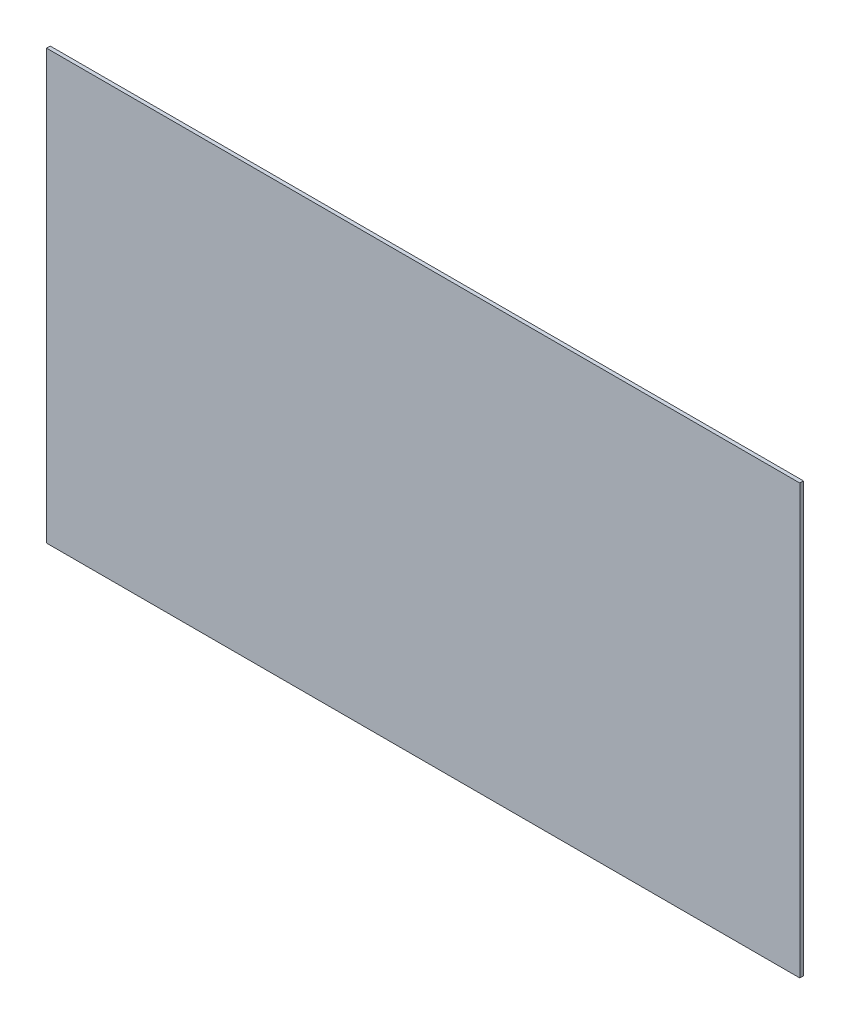
SolidWorks part; units mm, degrees
ref_plane "前视基准面" through (0, 0, 0) normal (0, 0, 1) x (1, 0, 0)
ref_plane "上视基准面" through (0, 0, 0) normal (0, 1, 0) x (1, 0, 0)
ref_plane "右视基准面" through (0, 0, 0) normal (1, 0, 0) x (0, 0, -1)
sketch "草图1" plane through (0, 0, 0) normal (0, 0, 1) x (1, 0, 0)
  line L1 (0, 0) -> (615, 0)
  line L2 (0, 0) -> (0, 350)
  line L3 (0, 350) -> (615, 350)
  line L4 (615, 0) -> (615, 350)
  dimension "D1" = 350
  dimension "D2" = 615
extrude "凸台-拉伸1" add sketch "草图1" along normal blind 3
